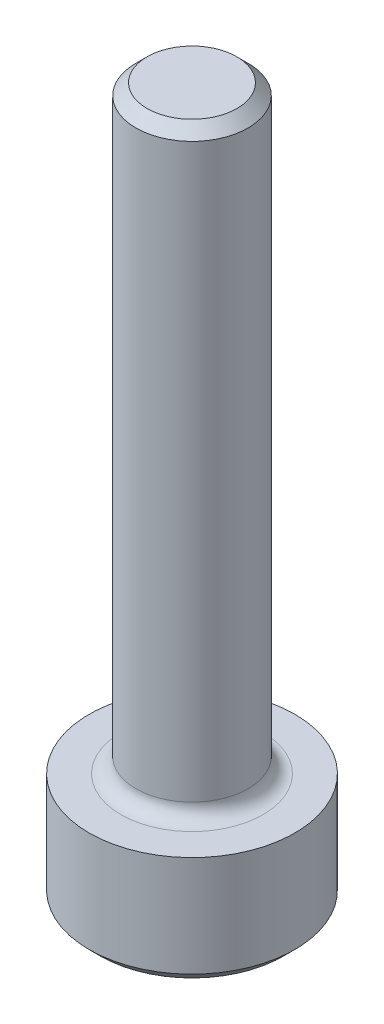
SolidWorks part; units mm, degrees
ref_plane "Front Plane" through (0, 0, 0) normal (0, 0, 1) x (1, 0, 0)
ref_plane "Top Plane" through (0, 0, 0) normal (0, 1, 0) x (1, 0, 0)
ref_plane "Right Plane" through (0, 0, 0) normal (1, 0, 0) x (0, 0, -1)
sketch "Sketch2" plane through (0, 0, 0) normal (0, 1, 0) x (1, 0, 0)
  circle A0 centre (0, 0) radius 1.5
extrude "Boss-Extrude1" add sketch "Sketch2" along normal blind 16
sketch "Sketch3" plane through (0, 0, 0) normal (0, 1, 0) x (1, 0, 0)
  circle A0 centre (0, 0) radius 2.75
  dimension "D1" = 5.5
extrude "Boss-Extrude2" add sketch "Sketch3" against normal blind 3
fillet "Fillet1" radius 0.4 1 edges at (0, 0, 1.5)
chamfer "Chamfer1" distance 0.3 angle 45 2 edges at (0, 16, 1.5) (0, -3, 2.75)
sketch "Sketch4" plane through (0, -3, 0) normal (0, -1, 0) x (1, 0, 0)
  line L1 (0, 1.4434) -> (-1.25, 0.7217)
  line L2 (-1.25, 0.7217) -> (-1.25, -0.7217)
  line L3 (-1.25, -0.7217) -> (0, -1.4434)
  line L4 (0, -1.4434) -> (1.25, -0.7217)
  line L5 (1.25, -0.7217) -> (1.25, 0.7217)
  line L6 (1.25, 0.7217) -> (0, 1.4434)
  circle A0 centre (0, 0) radius 1.25 construction
  dimension "D1" = 2.5
extrude "Cut-Extrude1" cut sketch "Sketch4" against normal blind 2.5
